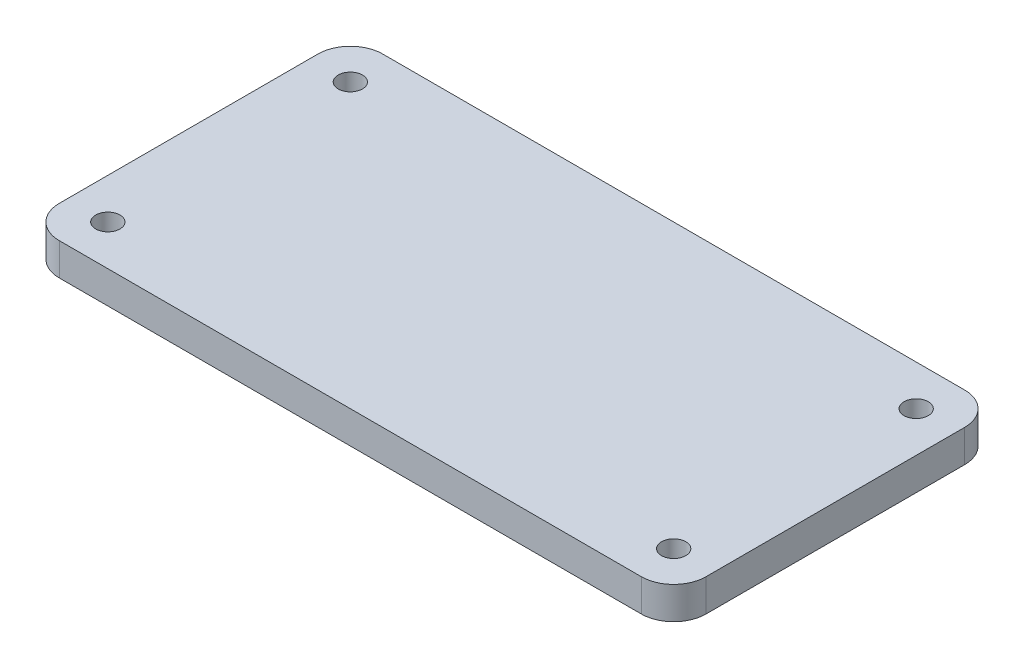
SolidWorks part; units mm, degrees
ref_plane "Front Plane" through (0, 0, 0) normal (0, 0, 1) x (1, 0, 0)
ref_plane "Top Plane" through (0, 0, 0) normal (0, 1, 0) x (1, 0, 0)
ref_plane "Right Plane" through (0, 0, 0) normal (1, 0, 0) x (0, 0, -1)
sketch "Sketch1" plane through (0, 0, 0) normal (0, 1, 0) x (1, 0, 0)
  line L0 (-40, 0) -> (40, 0) construction
  line L1 (-40, -20) -> (40, -20)
  line L2 (-40, -20) -> (-40, 20)
  line L3 (-40, 20) -> (40, 20)
  line L4 (40, -20) -> (40, 20)
  line L5 (0, 20) -> (0, -20) construction
  circle A0 centre (-35, 15) radius 1.5
  circle A1 centre (35, 15) radius 1.5
  circle A2 centre (35, -15) radius 1.5
  circle A3 centre (-35, -15) radius 1.5
  point P7 (0, 20)
  dimension "D3" = 3
  dimension "D4" = 5
  dimension "D5" = 5
  dimension "D1" = 80
  dimension "D2" = 40
extrude "Boss-Extrude1" add sketch "Sketch1" along normal blind 4
fillet "Fillet1" radius 4 4 edges at (-40, 2, 20) (-40, 2, -20) (40, 2, -20) (40, 2, 20)
